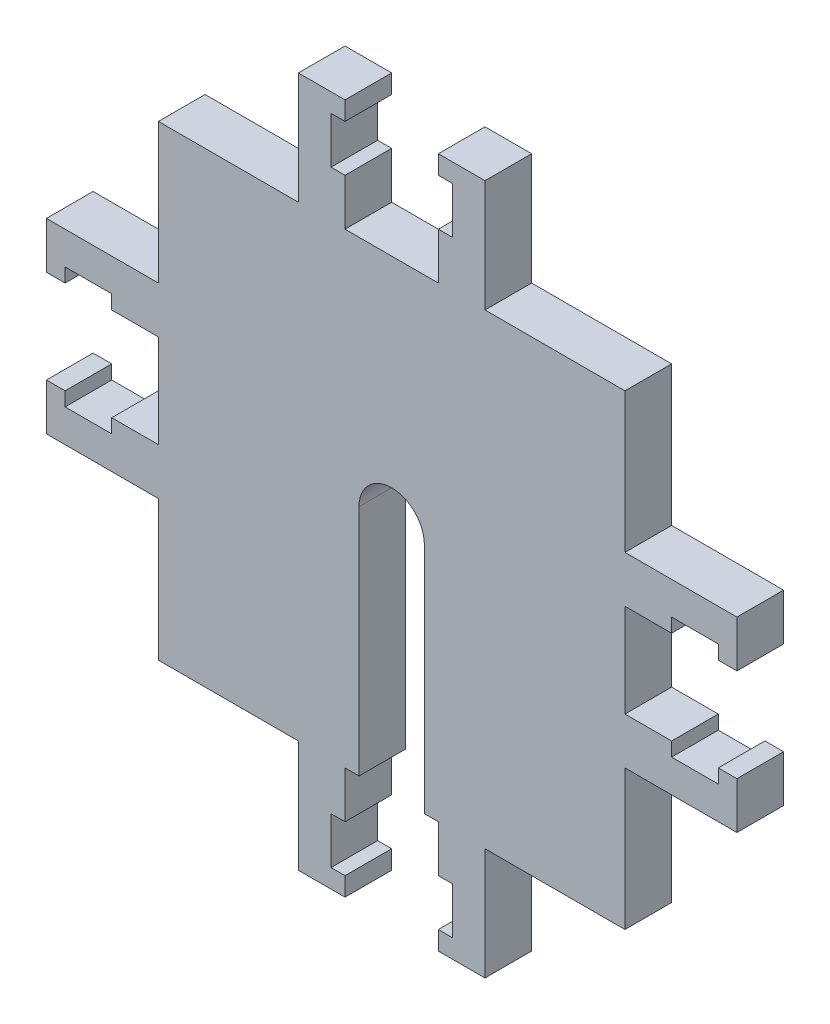
SolidWorks part; units mm, degrees
ref_plane "Plan de face" through (0, 0, 0) normal (0, 0, 1) x (1, 0, 0)
ref_plane "Plan de dessus" through (0, 0, 0) normal (0, 1, 0) x (1, 0, 0)
ref_plane "Plan de droite" through (0, 0, 0) normal (1, 0, 0) x (0, 0, -1)
sketch "Esquisse1" plane through (0, 0, 0) normal (0, 0, 1) x (1, 0, 0)
  line L0 (0, -10.9037) -> (0, 0) construction
  line L1 (0, 0) -> (78.1485, 0) construction
  line L2 (-25, 25) -> (-10, 25)
  line L3 (0, 0) -> (90.4553, 90.4553) construction
  line L4 (10, 25) -> (25, 25)
  line L5 (-25, -25) -> (-10, -25)
  line L6 (25, -25) -> (25, -10)
  line L8 (25, 10) -> (25, 25)
  line L9 (-25, -25) -> (-25, -10)
  line L10 (-25, 10) -> (-25, 25)
  line L11 (-3.5, 0) -> (-3.5, -25)
  line L13 (10, -25) -> (25, -25)
  line L15 (3.5, 0) -> (3.5, -25)
  line L18 (-3.5, -25) -> (3.5, -25)
  circle A0 centre (0, 0) radius 1.95 construction
  arc A7 (-3.5, 0) -> (3.5, 0) centre (0, 0) cw
  line B0 (0, -25) -> (0, -13.135) construction
  line B1 (0, -25) -> (-5, -25)
  line B2 (-5, -30) -> (-10, -30) construction
  line B3 (-10, -30) -> (-10, -25)
  line B4 (-5, -30) -> (-5, -25)
  line B5 (0, -25) -> (5, -25)
  line B6 (5, -25) -> (5, -30)
  line B7 (5, -30) -> (10, -30) construction
  line B8 (10, -30) -> (10, -25)
  line B9 (-10, -30) -> (-10, -37)
  line B10 (-10, -37) -> (-5, -37)
  line B11 (-5, -37) -> (-5, -35)
  line B12 (-5, -35) -> (-6.5, -35)
  line B13 (-6.5, -35) -> (-6.5, -30)
  line B14 (-6.5, -30) -> (-5, -30)
  line B15 (5, -35) -> (6.5, -35)
  line B16 (10, -37) -> (5, -37)
  line B17 (5, -37) -> (5, -35)
  line B18 (6.5, -35) -> (6.5, -30)
  line B19 (10, -30) -> (10, -37)
  line B20 (10, -30) -> (10, -25)
  line B21 (5, -30) -> (6.5, -30)
  line B22 (0, -25) -> (0, -13.135) construction
  line B23 (0, -25) -> (5, -25)
  line B24 (5, -30) -> (10, -30) construction
  line B25 (10, -30) -> (10, -25)
  line B26 (5, -30) -> (5, -25)
  line B27 (0, -25) -> (-5, -25)
  line B28 (-5, -25) -> (-5, -30)
  line B29 (-5, -30) -> (-10, -30) construction
  line B30 (-10, -30) -> (-10, -25)
  line B31 (10, -30) -> (10, -37)
  line B32 (10, -37) -> (5, -37)
  line B33 (5, -37) -> (5, -35)
  line B34 (5, -35) -> (6.5, -35)
  line B35 (6.5, -35) -> (6.5, -30)
  line B36 (6.5, -30) -> (5, -30)
  line B37 (-5, -35) -> (-6.5, -35)
  line B38 (-10, -37) -> (-5, -37)
  line B39 (-5, -37) -> (-5, -35)
  line B40 (-6.5, -35) -> (-6.5, -30)
  line B41 (-10, -30) -> (-10, -37)
  line B42 (-10, -30) -> (-10, -25)
  line B43 (-5, -30) -> (-6.5, -30)
  line B44 (0, 25) -> (0, 13.135) construction
  line B45 (0, 25) -> (-5, 25)
  line B46 (-5, 30) -> (-10, 30) construction
  line B47 (-10, 30) -> (-10, 25)
  line B48 (-5, 30) -> (-5, 25)
  line B49 (0, 25) -> (5, 25)
  line B50 (5, 25) -> (5, 30)
  line B51 (5, 30) -> (10, 30) construction
  line B52 (10, 30) -> (10, 25)
  line B53 (-10, 30) -> (-10, 37)
  line B54 (-10, 37) -> (-5, 37)
  line B55 (-5, 37) -> (-5, 35)
  line B56 (-5, 35) -> (-6.5, 35)
  line B57 (-6.5, 35) -> (-6.5, 30)
  line B58 (-6.5, 30) -> (-5, 30)
  line B59 (5, 35) -> (6.5, 35)
  line B60 (10, 37) -> (5, 37)
  line B61 (5, 37) -> (5, 35)
  line B62 (6.5, 35) -> (6.5, 30)
  line B63 (10, 30) -> (10, 37)
  line B64 (10, 30) -> (10, 25)
  line B65 (5, 30) -> (6.5, 30)
  line B66 (25, 0) -> (13.135, 0) construction
  line B67 (25, 0) -> (25, -5)
  line B68 (30, -5) -> (30, -10) construction
  line B69 (30, -10) -> (25, -10)
  line B70 (30, -5) -> (25, -5)
  line B71 (25, 0) -> (25, 5)
  line B72 (25, 5) -> (30, 5)
  line B73 (30, 5) -> (30, 10) construction
  line B74 (30, 10) -> (25, 10)
  line B75 (30, -10) -> (37, -10)
  line B76 (37, -10) -> (37, -5)
  line B77 (37, -5) -> (35, -5)
  line B78 (35, -5) -> (35, -6.5)
  line B79 (35, -6.5) -> (30, -6.5)
  line B80 (30, -6.5) -> (30, -5)
  line B81 (35, 5) -> (35, 6.5)
  line B82 (37, 10) -> (37, 5)
  line B83 (37, 5) -> (35, 5)
  line B84 (35, 6.5) -> (30, 6.5)
  line B85 (30, 10) -> (37, 10)
  line B86 (30, 10) -> (25, 10)
  line B87 (30, 5) -> (30, 6.5)
  line B88 (-25, 0) -> (-13.135, 0) construction
  line B89 (-25, 0) -> (-25, -5)
  line B90 (-30, -5) -> (-30, -10) construction
  line B91 (-30, -10) -> (-25, -10)
  line B92 (-30, -5) -> (-25, -5)
  line B93 (-25, 0) -> (-25, 5)
  line B94 (-25, 5) -> (-30, 5)
  line B95 (-30, 5) -> (-30, 10) construction
  line B96 (-30, 10) -> (-25, 10)
  line B97 (-30, -10) -> (-37, -10)
  line B98 (-37, -10) -> (-37, -5)
  line B99 (-37, -5) -> (-35, -5)
  line B100 (-35, -5) -> (-35, -6.5)
  line B101 (-35, -6.5) -> (-30, -6.5)
  line B102 (-30, -6.5) -> (-30, -5)
  line B103 (-35, 5) -> (-35, 6.5)
  line B104 (-37, 10) -> (-37, 5)
  line B105 (-37, 5) -> (-35, 5)
  line B106 (-35, 6.5) -> (-30, 6.5)
  line B107 (-30, 10) -> (-37, 10)
  line B108 (-30, 10) -> (-25, 10)
  line B109 (-30, 5) -> (-30, 6.5)
  dimension "D11" = 3.9
  dimension "D4" = 7
  dimension "D2" = 50
  dimension "D3" = 50
  dimension "D5" = 45
sketch_block_instance "Insert plots ep 5mm avec ergots-1"
sketch_block "Insert plots ep 5mm avec ergots" parameters "D1"=10, "D2"=5, "D3"=5, "D4"=5, "D5"=2, "D6"=1.5, "D7"=2, "D8"=2, "D9"=2.0716, "D10"=2
sketch_block_instance "Insert plots ep 5mm avec ergots-3"
sketch_block_instance "Insert plots ep 5mm avec ergots-4"
sketch_block_instance "Insert plots ep 5mm avec ergots-6"
sketch_block_instance "Insert plots ep 5mm avec ergots-7"
extrude "Boss.-Extru.1" add sketch "Esquisse1" along normal blind 5
